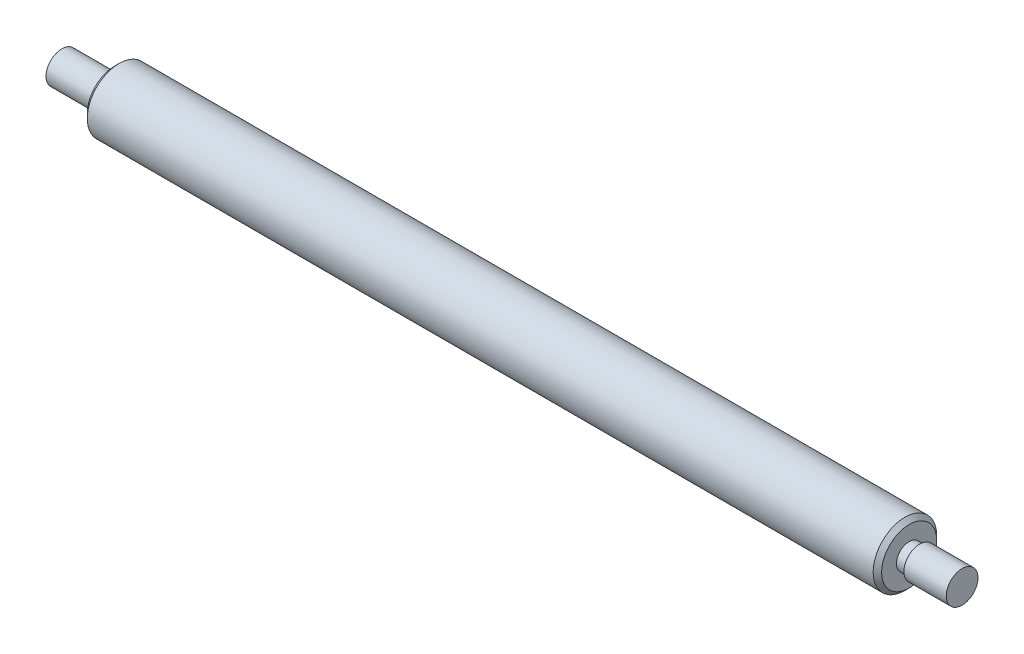
SolidWorks part; units mm, degrees
material "A2017"
ref_plane "Front Plane" through (0, 0, 0) normal (0, 0, 1) x (1, 0, 0)
ref_plane "Top Plane" through (0, 0, 0) normal (0, 1, 0) x (1, 0, 0)
ref_plane "Right Plane" through (0, 0, 0) normal (1, 0, 0) x (0, 0, -1)
sketch "Sketch1" plane through (0, 0, 0) normal (0, 0, 1) x (1, 0, 0)
  line L0 (0, 0) -> (75, 0) construction
  line L3 (0, 0) -> (0, 3)
  line L4 (0, 3) -> (75, 3)
  line L5 (75, 3) -> (75, 0)
  line L6 (75, 0) -> (0, 0)
  dimension "D" = 6
  dimension "L" = 75
revolve "Revolve1" add sketch "Sketch1" angle 360 about L0
chamfer "Chamfer1" distance 0.4 angle 45 1 edges at (0, 0, 3)
ref_plane "Dim. SC" through (6, 0, 0) normal (1, 0, 0) x (0, 0, -1)
sketch "Sketch2" [suppressed] plane through (0, 0, 0) normal (0, 0, 1) x (1, 0, 0)
  line L0 (-1.6, 2) -> (-1.6, 0) construction
  line L1 (26, 0) -> (-8, 0) construction
  line L2 (26, 0) -> (26, 2)
  line L3 (0, 2) -> (-8, 2)
  line L4 (-8, 0) -> (-8, 2)
  line L5 (26, 2) -> (21.2, 2)
  line L6 (21.2, 2) -> (21.2, 1.6)
  line L7 (21.2, 1.6) -> (20, 1.6)
  line L8 (20, 1.6) -> (20, 0)
  line L9 (20, 0) -> (26, 0)
  line L10 (0, 2) -> (0, 0)
  line L11 (0, 0) -> (-8, 0)
  line L12 (20, 4) -> (20, 0) construction
  dimension "M" = 3
  dimension "A" = 1
  dimension "F" = 5
  dimension "N" = 3
  dimension "NC" = 2.4
  dimension "Nx1.5" = 6
  dimension "G_s" = 1
revolve "Revolve2" [suppressed] add sketch "Sketch2" angle 360 about L1
cosmetic thread "Cosmetic Thread1" [suppressed] parameters "D1"=4, "TD_s"=3.242
cosmetic thread "Cosmetic Thread2" [suppressed] parameters "TD_s"=3.242
fillet "Fillet1" [suppressed] radius 0.5
chamfer "Chamfer2" [suppressed] distance 0.4 angle 45
sketch "Sketch3" [suppressed] plane through (0, 0, 0) normal (0, 0, 1) x (1, 0, 0)
  line L0 (-1.6, 2) -> (-1.6, 0) construction
  line L1 (26, 0) -> (-8, 0) construction
  line L2 (26, 0) -> (26, 2)
  line L3 (0, 2) -> (-8, 2)
  line L4 (-8, 0) -> (-8, 2)
  line L5 (26, 2) -> (21.2, 2)
  line L6 (21.2, 2) -> (21.2, 1.5)
  line L7 (21.2, 1.5) -> (20, 1.5)
  line L8 (20, 1.5) -> (20, 0)
  line L9 (20, 0) -> (26, 0)
  line L10 (0, 2) -> (0, 0)
  line L11 (0, 0) -> (-8, 0)
  line L13 (20, 4) -> (20, 0) construction
  dimension "M" = 3
  dimension "A" = 1
  dimension "F" = 5
  dimension "N" = 3
  dimension "NC" = 2.4
  dimension "Nx1.5" = 6
  dimension "G_s" = 1
revolve "Revolve3" [suppressed] add sketch "Sketch3" angle 360 about L1
cosmetic thread "Cosmetic Thread3" [suppressed] parameters "D1"=4, "TD_s"=3.242
cosmetic thread "Cosmetic Thread4" [suppressed] parameters "TD_s"=3.242
fillet "Fillet2" [suppressed] radius 0.5
chamfer "Chamfer3" [suppressed] distance 0.4 angle 45
sketch "Sketch4" [suppressed] plane through (0, 0, 0) normal (0, 1, 0) x (1, 0, 0)
  line L0 (10, -3.5) -> (10, -4) construction
  line L1 (6, 4) -> (14, 4)
  line L2 (6, 4) -> (6, 3.5)
  line L3 (6, 3.5) -> (14, 3.5)
  line L4 (14, 4) -> (14, 3.5)
  line L5 (6, -4) -> (14, -4)
  line L6 (6, -4) -> (6, -3.5)
  line L7 (6, -3.5) -> (14, -3.5)
  line L8 (14, -4) -> (14, -3.5)
  line L12 (0, 0) -> (20, 0) construction
  line L17 (6, -4.4) -> (6, 4.4) construction
  dimension "W" = 7
  dimension "L1_s" = 8
  dimension "D" = 6
  dimension "L1_s_L" = 8
extrude "Cut-Extrude1" [suppressed] cut sketch "Sketch4" against normal through all and the other way through all
ref_plane "Both Ends Threaded, Wrench Flats_SEC" [suppressed] through (10, 0, 0) normal (1, 0, 0) x (0, 0, -1)
sketch "Sketch5" plane through (0, 0, 0) normal (0, 0, 1) x (1, 0, 0)
  line L0 (-1, 1.5) -> (-1, 0) construction
  line L1 (80, 0) -> (-5, 0) construction
  line L2 (80, 0) -> (80, 1.5)
  line L3 (-5, 1.5) -> (0, 1.5)
  line L4 (-5, 0) -> (-5, 1.5)
  line L5 (76, 1.5) -> (80, 1.5)
  line L6 (76, 1.5) -> (76, 1.2)
  line L7 (76, 1.2) -> (75, 1.2)
  line L8 (75, 1.2) -> (75, 0)
  line L9 (75, 0) -> (80, 0)
  line L10 (0, 1.5) -> (0, 0)
  line L11 (0, 0) -> (-5, 0)
  line L13 (75, 3) -> (75, 0) construction
  dimension "M" = 3
  dimension "A" = 1
  dimension "F" = 5
  dimension "N" = 3
  dimension "NC" = 2.4
  dimension "G" = 5
  dimension "G_s" = 1
revolve "Revolve4" add sketch "Sketch5" angle 360 about L1
cosmetic thread "Cosmetic Thread5"
cosmetic thread "Cosmetic Thread6"
fillet "Fillet3" radius 0.5 1 edges at (0, 1.5, 0)
chamfer "Chamfer4" distance 0.4 angle 45 1 edges at (75, 0, 3)
sketch "Sketch6" [suppressed] plane through (0, 0, 0) normal (0, 0, 1) x (1, 0, 0)
  line L0 (-1.6, 2) -> (-1.6, 0) construction
  line L1 (28, 0) -> (-8, 0) construction
  line L2 (28, 0) -> (28, 2)
  line L3 (-8, 2) -> (0, 2)
  line L4 (-8, 0) -> (-8, 2)
  line L5 (21.2, 2) -> (28, 2)
  line L6 (21.2, 2) -> (21.2, 1.5)
  line L7 (21.2, 1.5) -> (20, 1.5)
  line L8 (20, 1.5) -> (20, 0)
  line L9 (20, 0) -> (28, 0)
  line L10 (0, 2) -> (0, 0)
  line L11 (0, 0) -> (-8, 0)
  line L12 (20, 4) -> (20, 0) construction
  dimension "M" = 3
  dimension "A" = 1
  dimension "F" = 5
  dimension "N" = 3
  dimension "NC" = 2.4
  dimension "G" = 5
  dimension "G_s" = 1
revolve "Revolve5" [suppressed] add sketch "Sketch6" angle 360 about L1
cosmetic thread "Cosmetic Thread7" [suppressed] parameters "D1"=4, "TD_s"=3.242
cosmetic thread "Cosmetic Thread8" [suppressed] parameters "TD_s"=3.242
fillet "Fillet4" [suppressed] radius 0.5
chamfer "Chamfer5" [suppressed] distance 0.4 angle 45
sketch "Sketch7" [suppressed] plane through (0, 0, 0) normal (0, 1, 0) x (1, 0, 0)
  line L0 (6, -4.4) -> (6, 4.4) construction
  line L1 (6, 4) -> (14, 4)
  line L2 (6, 4) -> (6, 3.5)
  line L3 (6, 3.5) -> (14, 3.5)
  line L4 (14, 4) -> (14, 3.5)
  line L5 (6, -4) -> (14, -4)
  line L6 (6, -4) -> (6, -3.5)
  line L7 (6, -3.5) -> (14, -3.5)
  line L8 (14, -4) -> (14, -3.5)
  line L9 (10, -3.5) -> (10, -4) construction
  line L12 (0, 0) -> (20, 0) construction
  dimension "W" = 7
  dimension "L1_s" = 8
  dimension "D" = 6
  dimension "L1_s_L" = 8
extrude "Cut-Extrude2" [suppressed] cut sketch "Sketch7" against normal through all and the other way through all
ref_plane "Both Ends Threaded, Thread Length Dia. Configurable, Wrench Flats_SEC" [suppressed] through (10, 0, 0) normal (1, 0, 0) x (0, 0, -1)
sketch "Sketch8" [suppressed] plane through (0, 0, 0) normal (0, 0, 1) x (1, 0, 0)
  line L0 (0, 0) -> (-1.6, 0) construction
  line L1 (-1.6, 4) -> (0, 4)
  line L2 (-1.6, 4) -> (-1.6, 1.5)
  line L3 (-1.6, 1.5) -> (0, 1.5)
  line L4 (0, 4) -> (0, 1.5)
  line L7 (0, 0) -> (0, 4) construction
  line L8 (0, 4) -> (20, 4) construction
  dimension "MC" = 3.2
  dimension "A" = 1
revolve "Cut-Revolve1" [suppressed] cut sketch "Sketch8" angle 360 about L0
ref_plane "Plane1" [suppressed] through (0, 4, 0) normal (0, 1, 0) x (1, 0, 0)
hole_wizard "Diameter Hole1" [suppressed] positions "Sketch10" profile "Sketch9" hole size "Ø2.5" standard "JIS"
sketch "Sketch10" [suppressed] plane through (0, 4, 0) normal (0, 1, 0) x (1, 0, 0)
  point P0 (7, 0)
  dimension "HL" = 7
sketch "Sketch9" [suppressed] plane through (7, 4, 0) normal (1, 0, 0) x (0, 0, 1)
  line L0 (0, 0) -> (0, 8)
  line L1 (0, 8) -> (1.25, 8)
  line L2 (1.25, 8) -> (1.25, 0)
  line L5 (1.25, 0) -> (0, 0)
  line L11 (0, 0) -> (0, 8) construction
  dimension "D_s" = 2.5
  dimension "Thru Hole Depth" = 8
equation "\"D1@Cosmetic Thread1\"=\"F@Sketch2\" - \"A@Sketch2\""
equation "\"Plane dim\"= \"D@Sketch1\" * 0.5"
equation "\"D1@Cosmetic Thread3\"=\"F@Sketch3\" - \"A@Sketch3\""
equation "\"D1@Cosmetic Thread5\"=\"F@Sketch5\" - \"A@Sketch5\""
equation "\"D1@Cosmetic Thread7\"=\"F@Sketch6\" - \"A@Sketch6\""
